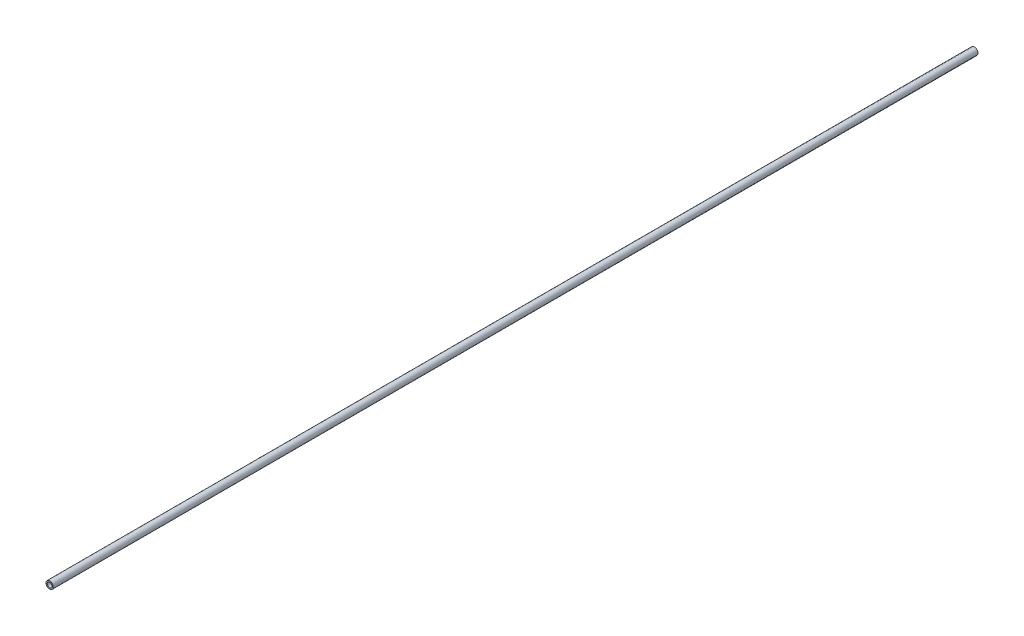
SolidWorks part; units mm, degrees
ref_plane "Front Plane" through (0, 0, 0) normal (0, 0, 1) x (1, 0, 0)
ref_plane "Top Plane" through (0, 0, 0) normal (0, 1, 0) x (1, 0, 0)
ref_plane "Right Plane" through (0, 0, 0) normal (1, 0, 0) x (0, 0, -1)
sketch "Sketch1" plane through (0, 0, 0) normal (0, 0, 1) x (1, 0, 0)
  circle A0 centre (0, 0) radius 4.7625
  circle A1 centre (0, 0) radius 3.175
  dimension "D1" = 9.525
  dimension "D2" = 6.35
extrude "Boss-Extrude1" add sketch "Sketch1" along normal blind 1219.2
equation "\"span\"= 48"
equation "\"wing_chord\"= 9"
equation "\"fuse_len\"= 15"
equation "\"fuse_height\"= 5"
equation "\"fuse_wid\"= 5"
equation "\"foam_t\"= 0.1875"
equation "\"main_spar_len\"= 36"
equation "\"x_fuse_to_wing\"= 3"
equation "\"x_cg_from_le\"= 2.25"
equation "\"boom_len\"= 30"
equation "\"D1@Boss-Extrude1\"=\"wing_spar_l\""
equation "\"wing_spar_d\"= 0.375"
equation "\"wing_spar_spacing\"= 1.35"
equation "\"D1@Sketch1\"=\"wing_spar_d\""
equation "\"wing_spar_l\"= 48"
equation "\"wing_angle\"= 1.5"
equation "\"boom_d\"= 0.75"
equation "\"wing_mount_l\"= 2.5"
equation "\"boom_mount_l\"= 1"
equation "\"vstab_span\"= 6.5"
equation "\"hstab_span\"= 15.25"
equation "\"tail_chord\"= 5"
equation "\"wing_spar_ID\"= 0.25"
equation "\"D2@Sketch1\"=\"wing_spar_ID\""
